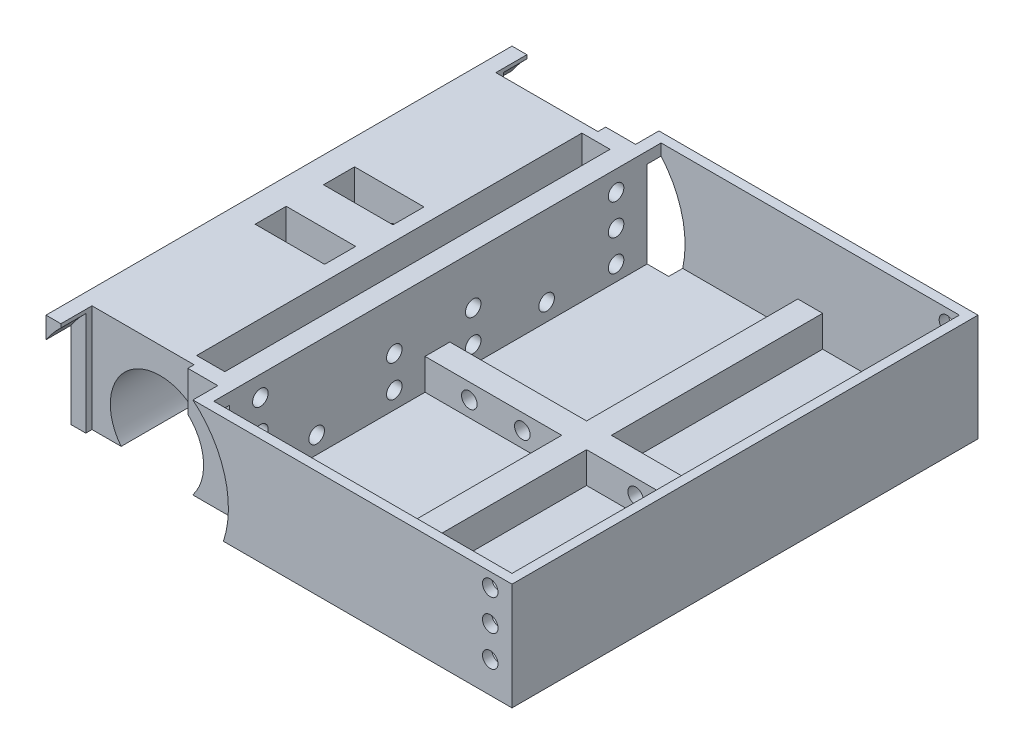
SolidWorks part; units mm, degrees
ref_plane "Plan de face" through (0, 0, 0) normal (0, 0, 1) x (1, 0, 0)
ref_plane "Plan de dessus" through (0, 0, 0) normal (0, 1, 0) x (1, 0, 0)
ref_plane "Plan de droite" through (0, 0, 0) normal (1, 0, 0) x (0, 0, -1)
sketch "Cube" plane through (0, 0, 0) normal (0, 1, 0) x (1, 0, 0)
  line L1 (-109.2105, 63.4868) -> (40.7895, 63.4868)
  line L2 (-109.2105, 63.4868) -> (-109.2105, -86.5132)
  line L3 (-109.2105, -86.5132) -> (40.7895, -86.5132)
  line L4 (40.7895, 63.4868) -> (40.7895, -86.5132)
  dimension "D1" = 150
  dimension "D2" = 150
extrude "Boss.-Extru.1" add sketch "Cube" along normal blind 34.5
sketch "Pave" plane through (0, 34.5, 0) normal (0, 1, 0) x (1, 0, 0)
  line L0 (40.7895, -86.5132) -> (40.7895, 63.4868) construction
  line L1 (-109.2105, -86.5132) -> (40.7895, -86.5132) construction
  line L2 (40.7895, 63.4868) -> (-109.2105, 63.4868) construction
  line L4 (37.7895, -83.5132) -> (-58.2105, -83.5132)
  line L5 (37.7895, -83.5132) -> (37.7895, 60.4868)
  line L6 (37.7895, 60.4868) -> (-58.2105, 60.4868)
  line L7 (-58.2105, -83.5132) -> (-58.2105, 60.4868)
  point P0 (37.7895, -83.5132)
  point P5 (-58.2105, 60.4868)
  dimension "D1" = 3
  dimension "D2" = 3
  dimension "D3" = 3
  dimension "D4" = 99
extrude "Enlèv. mat.-Extru.1" cut sketch "Pave" against normal blind 31.5
sketch "Vis1" plane through (0, 0, 86.5132) normal (0, 0, 1) x (1, 0, 0)
  line L0 (40.7895, 34.5) -> (40.7895, 0) construction
  line L1 (-109.2105, 0) -> (40.7895, 0) construction
  circle A0 centre (33.7895, 10) radius 2.5
  circle A1 centre (33.7895, 20) radius 2.5
  circle A2 centre (33.7895, 30) radius 2.5
  point P0 (33.7895, 10)
  point P3 (33.7895, 20)
  point P4 (33.7895, 30)
  dimension "D1" = 7
  dimension "D2" = 7
  dimension "D3" = 7
  dimension "D4" = 10
  dimension "D5" = 20
  dimension "D6" = 30
extrude "Enlèv. mat.-Extru.2" cut sketch "Vis1" against normal blind 5
sketch "Vis2" plane through (0, 0, -63.4868) normal (0, 0, -1) x (-1, 0, 0)
  line L0 (-40.7895, 34.5) -> (-40.7895, 0) construction
  line L1 (-40.7895, 0) -> (109.2105, 0) construction
  circle A0 centre (-33.7895, 10) radius 2.5
  circle A1 centre (-33.7895, 20) radius 2.5
  circle A2 centre (-33.7895, 30) radius 2.5
  point P0 (-33.7895, 10)
  point P1 (-33.7895, 20)
  point P2 (-33.7895, 30)
  dimension "D1" = 7
  dimension "D2" = 7
  dimension "D3" = 7
  dimension "D4" = 10
  dimension "D5" = 20
  dimension "D6" = 30
extrude "Enlèv. mat.-Extru.3" cut sketch "Vis2" against normal blind 5
sketch "Pave proche moteur" plane through (0, 34.5, 0) normal (0, 1, 0) x (1, 0, 0)
  line L0 (-109.2105, -86.5132) -> (40.7895, -86.5132) construction
  line L1 (-58.2105, 60.4868) -> (-58.2105, -83.5132) construction
  line L2 (40.7895, 63.4868) -> (-109.2105, 63.4868) construction
  line L4 (-61.2105, 50.4868) -> (-73.7105, 50.4868)
  line L5 (-61.2105, 50.4868) -> (-61.2105, -73.5132)
  line L6 (-61.2105, -73.5132) -> (-73.7105, -73.5132)
  line L7 (-73.7105, 50.4868) -> (-73.7105, -73.5132)
  point P0 (-61.2105, -73.5132)
  point P5 (-61.2105, 50.4868)
  dimension "D1" = 13
  dimension "D2" = 3
  dimension "D3" = 13
  dimension "D4" = 3
  dimension "D5" = 12.5
extrude "Enlèv. mat.-Extru.4" cut sketch "Pave proche moteur" against normal blind 31.5
sketch "Pave Roue libre" plane through (0, 34.5, 0) normal (0, 1, 0) x (1, 0, 0)
  line L0 (40.7895, 63.4868) -> (-109.2105, 63.4868) construction
  line L1 (-58.2105, 60.4868) -> (-58.2105, -83.5132) construction
  line L2 (-109.2105, -86.5132) -> (40.7895, -86.5132) construction
  line L3 (-71.5505, 53.4868) -> (-104.4105, 53.4868)
  line L4 (-71.5505, 53.4868) -> (-71.5505, 69.1835)
  line L5 (-71.5505, 69.1835) -> (-104.4105, 69.1835)
  line L6 (-104.4105, 53.4868) -> (-104.4105, 69.1835)
  line L8 (-71.5505, -76.5132) -> (-104.4105, -76.5132)
  line L9 (-71.5505, -76.5132) -> (-71.5505, -94.9327)
  line L10 (-71.5505, -94.9327) -> (-104.4105, -94.9327)
  line L11 (-104.4105, -76.5132) -> (-104.4105, -94.9327)
  point P0 (-71.5505, 53.4868)
  point P9 (-71.5505, -76.5132)
  dimension "D1" = 10
  dimension "D2" = 13.34
  dimension "D3" = 32.86
  dimension "D4" = 13.34
  dimension "D5" = 10
extrude "Enlèv. mat.-Extru.5" cut sketch "Pave Roue libre" against normal blind 36
sketch "Cables" plane through (0, 34.5, 0) normal (0, 1, 0) x (1, 0, 0)
  line L0 (40.7895, 63.4868) -> (-71.5505, 63.4868) construction
  line L1 (-58.2105, 60.4868) -> (-58.2105, -83.5132) construction
  line L2 (-71.5505, -86.5132) -> (40.7895, -86.5132) construction
  line L3 (-58.2105, 60.4868) -> (-58.2105, -83.5132) construction
  line L5 (-100.8905, -5.5132) -> (-78.5305, -5.5132)
  line L6 (-100.8905, -5.5132) -> (-100.8905, 4.4868)
  line L7 (-100.8905, 4.4868) -> (-78.5305, 4.4868)
  line L8 (-78.5305, -5.5132) -> (-78.5305, 4.4868)
  line L9 (-100.8905, -17.5132) -> (-78.5305, -17.5132)
  line L10 (-100.8905, -17.5132) -> (-100.8905, -27.5132)
  line L11 (-100.8905, -27.5132) -> (-78.5305, -27.5132)
  line L12 (-78.5305, -17.5132) -> (-78.5305, -27.5132)
  point P0 (-100.8905, -5.5132)
  point P5 (-100.8905, -17.5132)
  dimension "D1" = 69
  dimension "D2" = 42.68
  dimension "D3" = 69
  dimension "D4" = 42.68
  dimension "D5" = 22.36
  dimension "D6" = 10
  dimension "D7" = 22.36
  dimension "D8" = 10
extrude "Enlèv. mat.-Extru.6" cut sketch "Cables" against normal blind 36
sketch "Roue ext" plane through (0, 0, 86.5132) normal (0, 0, 1) x (1, 0, 0)
  circle A0 centre (-82.5, 10) radius 32
  point P0 (-82.5, 10)
extrude "Enlèv. mat.-Extru.7" cut sketch "Roue ext" against normal blind 8
sketch "Roue inter" plane through (0, 0, 86.5132) normal (0, 0, 1) x (1, 0, 0)
  circle A0 centre (-82.5, 10) radius 16.02
  point P0 (-82.5, 10)
extrude "Enlèv. mat.-Extru.8" cut sketch "Roue inter" against normal blind 69
sketch "Roue ext2" plane through (0, 0, -63.4868) normal (0, 0, -1) x (-1, 0, 0)
  circle A0 centre (82.5, 10) radius 32
  point P0 (82.5, 10)
extrude "Enlèv. mat.-Extru.9" cut sketch "Roue ext2" against normal blind 7.5
sketch "Roue inter2" plane through (0, 0, -63.4868) normal (0, 0, -1) x (-1, 0, 0)
  circle A0 centre (82.5, 10) radius 16.02
  point P0 (82.5, 10)
extrude "Enlèv. mat.-Extru.10" cut sketch "Roue inter2" against normal blind 69
sketch "Vis Moteur pour support" plane through (-58.2105, 0, 0) normal (1, 0, 0) x (0, 0, -1)
  line L0 (55.9868, 3) -> (-78.5132, 3) construction
  line L1 (-78.5132, 3) -> (-78.5132, 30.8332) construction
  line L2 (55.9868, 30.8332) -> (55.9868, 3) construction
  circle A0 centre (-68.5132, 8) radius 2.5
  circle A1 centre (-68.5132, 18) radius 2.5
  circle A2 centre (-68.5132, 28) radius 2.5
  circle A3 centre (45.9868, 8) radius 2.5
  circle A4 centre (45.9868, 18) radius 2.5
  circle A5 centre (45.9868, 28) radius 2.5
  point P0 (-68.5132, 8)
  point P1 (-68.5132, 18)
  point P2 (-68.5132, 28)
  point P13 (45.9868, 18)
  point P14 (45.9868, 28)
  point P15 (45.9868, 8)
  dimension "D7" = 5
  dimension "D1" = 5
  dimension "D2" = 15
  dimension "D3" = 25
  dimension "D4" = 10
  dimension "D5" = 10
  dimension "D6" = 10
  dimension "D8" = 15
  dimension "D9" = 25
  dimension "D10" = 10
  dimension "D11" = 10
  dimension "D12" = 10
extrude "Enlèv. mat.-Extru.11" cut sketch "Vis Moteur pour support" against normal blind 10
sketch "Esquisse1" plane through (0, 3, 0) normal (0, 1, 0) x (1, 0, 0)
  line L0 (-58.2105, 55.9868) -> (-58.2105, -78.5132) construction
  line L1 (37.7895, 60.4868) -> (-51.275, 60.4868) construction
  line L2 (37.7895, -83.5132) -> (37.7895, 60.4868) construction
  line L3 (-58.2105, -15.5132) -> (-14.2105, -15.5132)
  line L4 (-58.2105, -15.5132) -> (-58.2105, -7.5132)
  line L5 (-58.2105, -7.5132) -> (-14.2105, -7.5132)
  line L6 (37.7895, -15.5132) -> (37.7895, -7.5132)
  line L7 (-51.275, -83.5132) -> (37.7895, -83.5132) construction
  line L8 (-14.2105, 60.4868) -> (-6.2105, 60.4868)
  line L9 (-14.2105, 60.4868) -> (-14.2105, -7.5132)
  line L10 (-14.2105, -83.5132) -> (-6.2105, -83.5132)
  line L11 (-6.2105, 60.4868) -> (-6.2105, -7.5132)
  line L12 (-14.2105, -15.5132) -> (-14.2105, -83.5132)
  line L13 (-6.2105, -15.5132) -> (37.7895, -15.5132)
  line L14 (-6.2105, -15.5132) -> (-6.2105, -83.5132)
  line L15 (-6.2105, -7.5132) -> (37.7895, -7.5132)
  point P0 (-58.2105, -11.5132)
  point P5 (-58.2105, -7.5132)
  point P6 (-58.2105, -15.5132)
  point P13 (-10.2105, 60.4868)
  point P14 (-14.2105, 60.4868)
  point P15 (-6.2105, 60.4868)
  dimension "D1" = 72
  dimension "D2" = 68
  dimension "D3" = 76
  dimension "D4" = 48
  dimension "D5" = 52
  dimension "D6" = 44
extrude "Boss.-Extru.2" add sketch "Esquisse1" along normal blind 10
sketch "Esquisse2" plane through (0, 0, 15.5132) normal (0, 0, 1) x (1, 0, 0)
  line L0 (-58.2105, 3) -> (-14.2105, 3) construction
  line L1 (-6.2105, 3) -> (37.7895, 3) construction
  circle A0 centre (-43.9429, 8) radius 2.5
  circle A1 centre (-26.8896, 8) radius 2.5
  circle A2 centre (9.5885, 8) radius 2.5
  circle A3 centre (23.5624, 8) radius 2.5
  point P0 (-43.9429, 8)
  point P1 (-26.8896, 8)
  point P4 (9.5885, 8)
  point P5 (23.5624, 8)
  dimension "D1" = 5
  dimension "D2" = 5
  dimension "D3" = 5
extrude "Enlèv. mat.-Extru.12" cut sketch "Esquisse2" against normal blind 10
sketch "Esquisse3" plane through (0, 3, 0) normal (0, 1, 0) x (1, 0, 0)
  line L0 (-68.0903, -73.5132) -> (-61.2105, -73.5132) construction
  line L1 (-61.2105, 50.4868) -> (-64.6504, 50.4868)
  line L2 (-61.2105, 50.4868) -> (-61.2105, -73.5132)
  line L3 (-61.2105, -73.5132) -> (-64.6504, -73.5132)
  line L4 (-64.6504, 50.4868) -> (-64.6504, -73.5132)
extrude "Boss.-Extru.3" add sketch "Esquisse3" along normal blind 31
sketch "Esquisse5" plane through (0, 34, 0) normal (0, 1, 0) x (1, 0, 0)
  line L1 (-61.2105, 50.4868) -> (-64.6504, 50.4868)
  line L2 (-61.2105, 50.4868) -> (-61.2105, -73.5132)
  line L3 (-61.2105, -73.5132) -> (-64.6504, -73.5132)
  line L4 (-64.6504, 50.4868) -> (-64.6504, -73.5132)
extrude "Boss.-Extru.4" add sketch "Esquisse5" along normal blind 0.5
sketch "Esquisse6" plane through (-58.2105, 0, 0) normal (1, 0, 0) x (0, 0, -1)
  circle A0 centre (-68.5132, 28) radius 2.5
  circle A1 centre (-68.5132, 18) radius 2.5
  circle A2 centre (-68.5132, 8) radius 2.5
  circle A3 centre (45.9868, 28) radius 2.5
  circle A4 centre (45.9868, 18) radius 2.5
  circle A5 centre (45.9868, 8) radius 2.5
extrude "Enlèv. mat.-Extru.13" cut sketch "Esquisse6" against normal blind 10
sketch "Esquisse7" plane through (-58.2105, 0, 0) normal (1, 0, 0) x (0, 0, -1)
  circle A0 centre (0, 8.5279) radius 2.5
  circle A2 centre (0, 18.7509) radius 2.5
  circle A3 centre (-25.4002, 8.5279) radius 2.5
  circle A4 centre (-25.4002, 18.7509) radius 2.5
  circle A5 centre (-50.3865, 8.5279) radius 2.5
  circle A6 centre (23.6295, 8.5279) radius 2.5
extrude "Enlèv. mat.-Extru.14" cut sketch "Esquisse7" against normal blind 10
sketch "Esquisse8" plane through (0, 3, 0) normal (0, 1, 0) x (1, 0, 0)
  line L0 (37.7895, -83.5132) -> (37.7895, -15.5132) construction
  line L1 (-58.2105, -83.5132) -> (37.7895, -83.5132) construction
  line L2 (37.7895, 60.4868) -> (-6.2105, 60.4868) construction
  circle A0 centre (19.7895, -43.5132) radius 2.5
  circle A1 centre (19.7895, 20.4868) radius 2.5
  point P0 (19.7895, -43.5132)
  point P7 (19.7895, 20.4868)
  dimension "D3" = 40
  dimension "D1" = 18
  dimension "D2" = 40
extrude "Enlèv. mat.-Extru.15" cut sketch "Esquisse8" against normal blind 10
